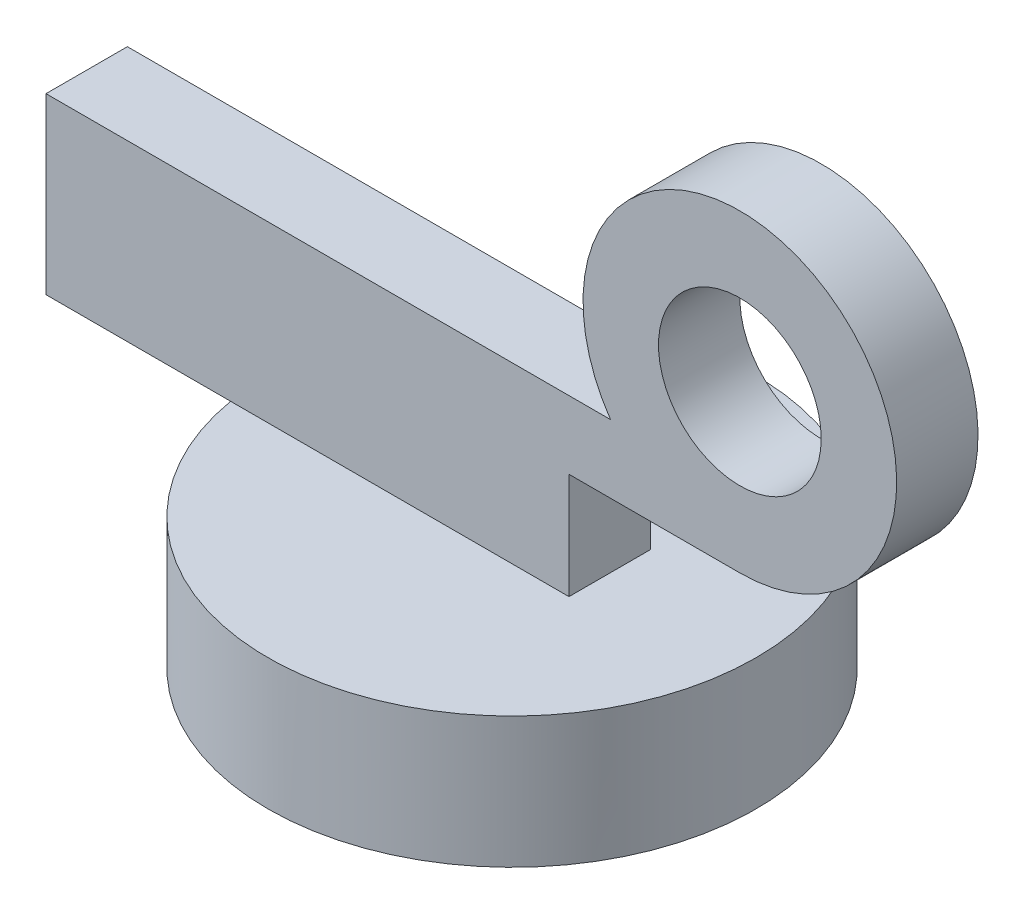
SolidWorks part; units mm, degrees
ref_plane "Front Plane" through (0, 0, 0) normal (0, 0, 1) x (1, 0, 0)
ref_plane "Top Plane" through (0, 0, 0) normal (0, 1, 0) x (1, 0, 0)
ref_plane "Right Plane" through (0, 0, 0) normal (1, 0, 0) x (0, 0, -1)
sketch "Sketch1" plane through (0, 0, 0) normal (0, 1, 0) x (1, 0, 0)
  circle A0 centre (0, 0) radius 300
extrude "Boss-Extrude1" add sketch "Sketch1" along normal blind 161 contours A0
sketch "Sketch2" plane through (0, 0, 0) normal (0, 0, 1) x (1, 0, 0)
  line L1 (-522.75, 161) -> (120, 161)
  line L2 (-522.75, 161) -> (-522.75, 375)
  line L3 (-522.75, 375) -> (120, 375)
  line L4 (120, 161) -> (120, 375)
  circle A0 centre (330, 484) radius 100
  circle A1 centre (330, 484) radius 192.75
extrude "Boss-Extrude2" add sketch "Sketch2" along normal mid plane 100
sketch "Sketch3" plane through (0, 0, 0) normal (0, -1, 0) x (1, 0, 0)
  circle A0 centre (0, 0) radius 75
extrude "Cut-Extrude1" cut sketch "Sketch3" against normal blind 40
sketch "Sketch4" plane through (0, 40, 0) normal (0, -1, 0) x (1, 0, 0)
  circle A0 centre (0, 0) radius 100
extrude "Cut-Extrude2" cut sketch "Sketch4" against normal blind 40
sketch "Sketch5" plane through (120, 0, 0) normal (1, 0, 0) x (0, 0, -1)
  line L5 (-50, 161) -> (-50, 375) construction
  line L6 (-50, 291.25) -> (50, 291.25)
  line L7 (-50, 291.25) -> (-50, 375)
  line L8 (-50, 375) -> (50, 375)
  line L9 (50, 291.25) -> (50, 375)
extrude "Boss-Extrude3" add sketch "Sketch5" along normal up to surface (210 mm away) contours L7 L8 L9 L6
